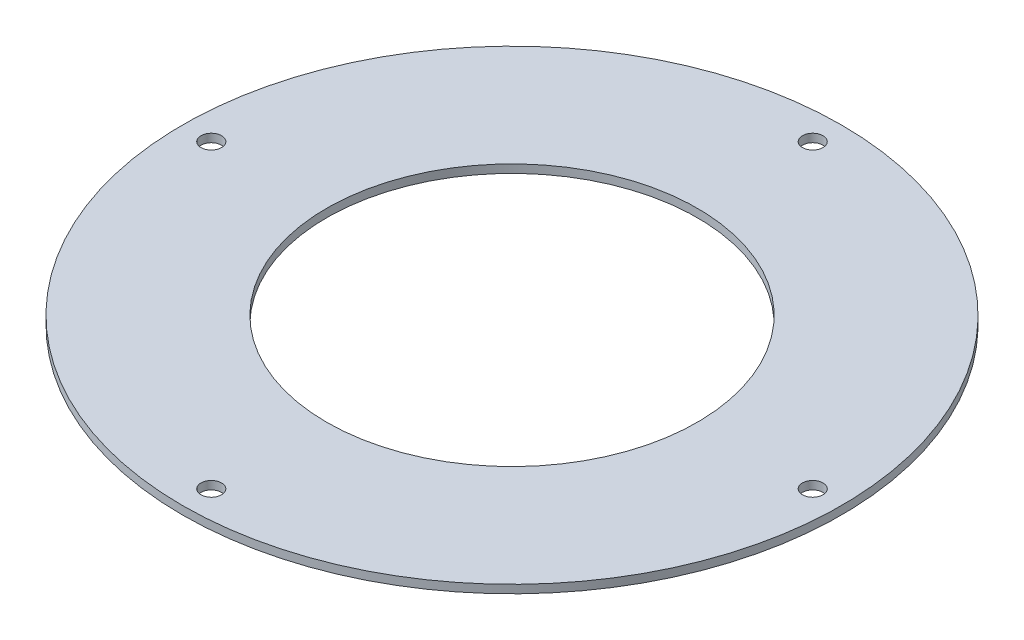
SolidWorks part; units mm, degrees
ref_plane "Front Plane" through (0, 0, 0) normal (0, 0, 1) x (1, 0, 0)
ref_plane "Top Plane" through (0, 0, 0) normal (0, 1, 0) x (1, 0, 0)
ref_plane "Right Plane" through (0, 0, 0) normal (1, 0, 0) x (0, 0, -1)
sketch "Sketch1" plane through (0, 0, 0) normal (0, 1, 0) x (1, 0, 0)
  circle A0 centre (0, 0) radius 80
  circle A1 centre (0, 0) radius 45
  dimension "D1" = 160
  dimension "D2" = 90
extrude "Boss-Extrude1" add sketch "Sketch1" along normal blind 2
sketch "Sketch2" plane through (0, 2, 0) normal (0, 1, 0) x (1, 0, 0)
  line L0 (0, 0) -> (0, 73) construction
  line L1 (0, 0) -> (73, 0) construction
  line L2 (0, 0) -> (0, -73) construction
  line L3 (0, 0) -> (-73, 0) construction
  circle A0 centre (0, 73) radius 2.5
  circle A1 centre (73, 0) radius 2.5
  circle A2 centre (0, -73) radius 2.5
  circle A3 centre (-73, 0) radius 2.5
  point P13 (0, 0)
  dimension "D2" = 5
  dimension "D1" = 73
  dimension "D3" = 4
extrude "Cut-Extrude1" cut sketch "Sketch2" against normal through all
